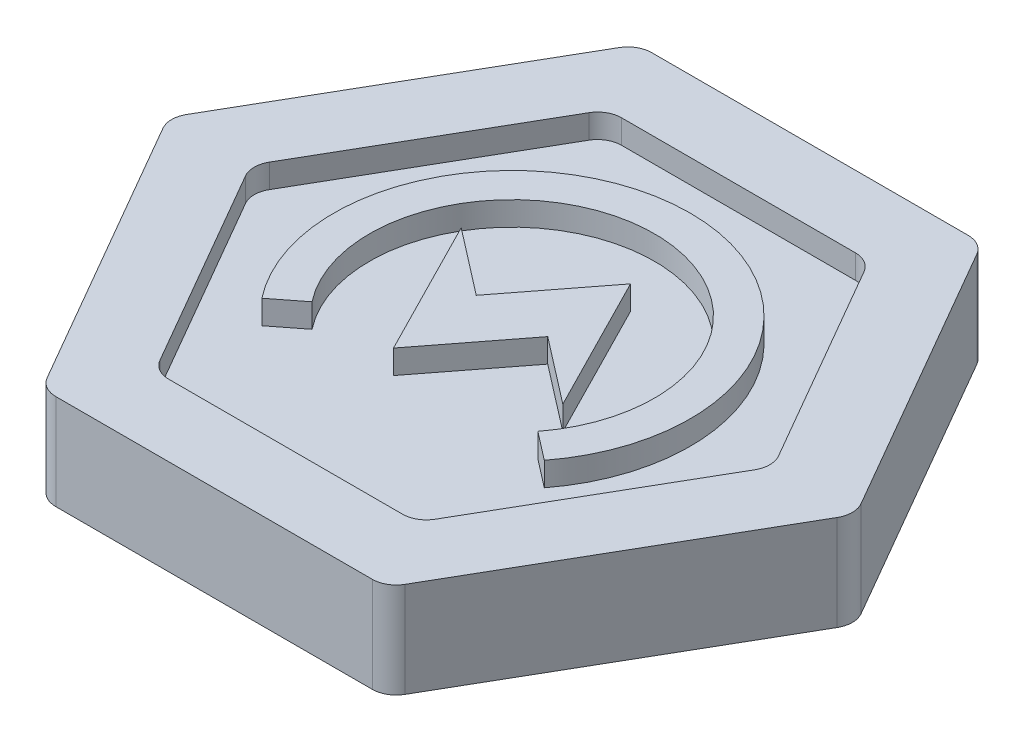
SolidWorks part; units mm, degrees
ref_plane "前视基准面" through (0, 0, 0) normal (0, 0, 1) x (1, 0, 0)
ref_plane "上视基准面" through (0, 0, 0) normal (0, 1, 0) x (1, 0, 0)
ref_plane "右视基准面" through (0, 0, 0) normal (1, 0, 0) x (0, 0, -1)
sketch "草图1" plane through (0, 0, 0) normal (0, 1, 0) x (1, 0, 0)
  line L1 (14.4338, 0) -> (7.2169, 12.5)
  line L2 (7.2169, 12.5) -> (-7.2169, 12.5)
  line L3 (-7.2169, 12.5) -> (-14.4338, 0)
  line L4 (-14.4338, 0) -> (-7.2169, -12.5)
  line L5 (-7.2169, -12.5) -> (7.2169, -12.5)
  line L6 (7.2169, -12.5) -> (14.4338, 0)
  circle A0 centre (0, 0) radius 12.5 construction
  dimension "D1" = 25
extrude "凸台-拉伸1" add sketch "草图1" along normal blind 4
sketch "草图2" plane through (0, 4, 0) normal (0, 1, 0) x (1, 0, 0)
  line L0 (5.4848, -9.5) -> (10.9697, 0)
  line L1 (10.9697, 0) -> (5.4848, 9.5)
  line L2 (5.4848, 9.5) -> (-5.4848, 9.5)
  line L3 (-5.4848, 9.5) -> (-10.9697, 0)
  line L4 (-10.9697, 0) -> (-5.4848, -9.5)
  line L5 (-5.4848, -9.5) -> (5.4848, -9.5)
  line L6 (7.2169, -12.5) -> (14.4338, 0)
  line L7 (14.4338, 0) -> (7.2169, 12.5)
  line L8 (7.2169, 12.5) -> (-7.2169, 12.5)
  line L9 (-7.2169, 12.5) -> (-14.4338, 0)
  line L10 (-14.4338, 0) -> (-7.2169, -12.5)
  line L11 (-7.2169, -12.5) -> (7.2169, -12.5)
  line L12 (7.2169, -12.5) -> (14.4338, 0)
  line L13 (14.4338, 0) -> (7.2169, 12.5)
  line L14 (7.2169, 12.5) -> (-7.2169, 12.5)
  line L15 (-7.2169, 12.5) -> (-14.4338, 0)
  line L16 (-14.4338, 0) -> (-7.2169, -12.5)
  line L17 (-7.2169, -12.5) -> (7.2169, -12.5)
  dimension "D1" = 0
  dimension "D2" = 3
extrude "切除-拉伸1" cut sketch "草图2" against normal blind 1 contours L0 L1 L2 L3 L4 L5
fillet "圆角1" radius 1 12 edges at (-10.9697, 3.5, 0) (-5.4848, 3.5, 9.5) (5.4848, 3.5, 9.5) (10.9697, 3.5, 0) (5.4848, 3.5, -9.5) (-5.4848, 3.5, -9.5) (-14.4338, 2, 0) (-7.2169, 2, -12.5) (7.2169, 2, -12.5) (14.4338, 2, 0) (7.2169, 2, 12.5) (-7.2169, 2, 12.5)
sketch "草图3" plane through (0, 3, 0) normal (0, 1, 0) x (1, 0, 0)
  line L0 (4.2705, -2.1387) -> (1.32, 3.653)
  line L1 (1.32, 3.653) -> (-1.5, 0)
  line L2 (-1.5, 0) -> (-4.2705, 2.1387)
  line L3 (-4.2705, 2.1387) -> (-1.32, -3.653)
  line L4 (-1.32, -3.653) -> (1.5, 0)
  line L5 (1.5, 0) -> (4.2705, -2.1387)
  line L6 (-1.5, 0) -> (1.5, 0) construction
  line L7 (4.7343, -3.6505) -> (5.9221, -4.5665)
  line L8 (-4.711, -3.6805) -> (-5.8931, -4.604)
  arc A0 (5.9221, -4.5665) -> (-5.8931, -4.604) centre (0, 0) ccw
  arc A1 (4.7343, -3.6505) -> (-4.711, -3.6805) centre (0, 0) ccw
  point P2 (0, 0)
  point P7 (-5.2762, -1.5911)
  point P9 (-5.4978, -4.2951)
  point P10 (5.9221, -4.604)
  dimension "D1" = 3
  dimension "D2" = 3.5
  dimension "D3" = 6.5
  dimension "D4" = 1.5
extrude "凸台-拉伸2" add sketch "草图3" along normal blind 1
